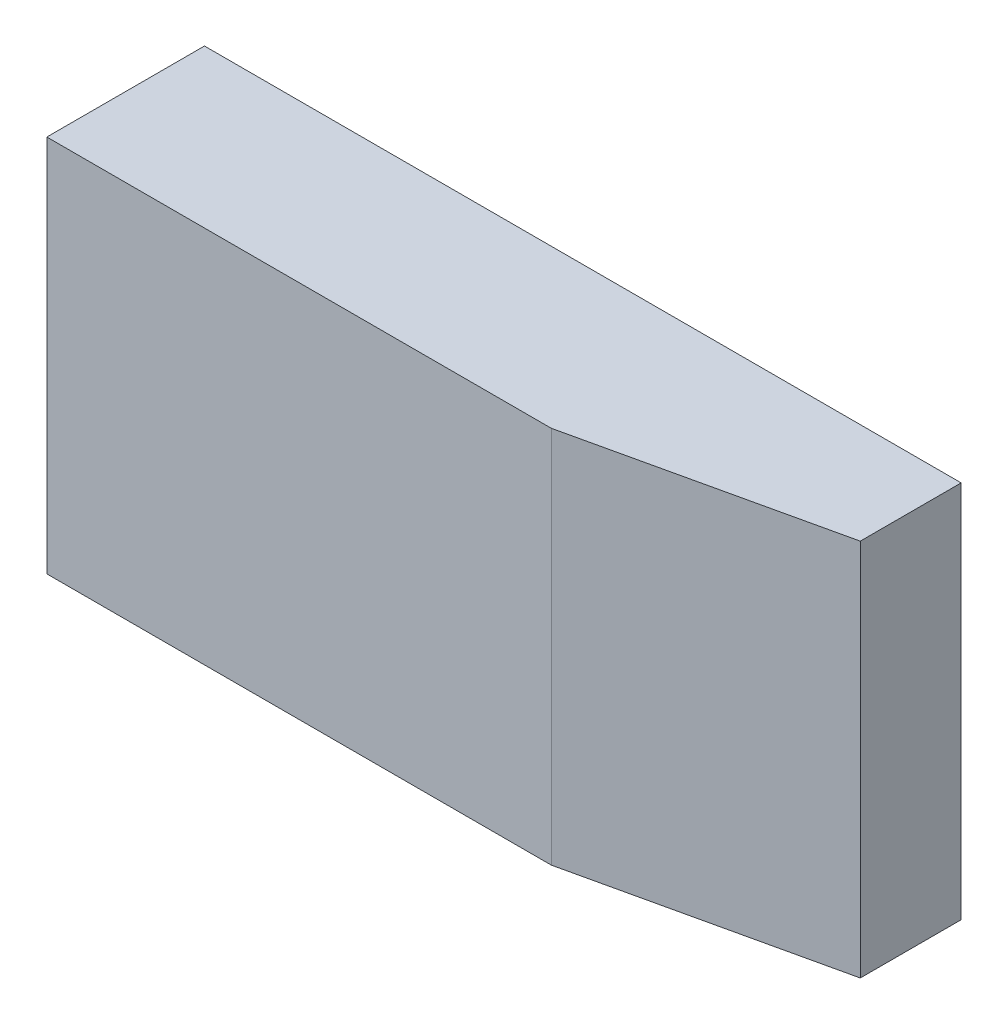
SolidWorks part; units mm, degrees
ref_plane "Front Plane" through (0, 0, 0) normal (1, 0, 0) x (0, 1, 0)
ref_plane "Top Plane" through (0, 0, 0) normal (0, 0, 1) x (0, 1, 0)
ref_plane "Right Plane" through (0, 0, 0) normal (0, 1, 0) x (-1, 0, 0)
sketch "Sketch1" plane through (0, 0, 0) normal (0, 1, 0) x (-1, 0, 0)
  line L0 (0, 0) -> (0, 8)
  line L1 (0, 8) -> (20, 12.5)
  line L2 (20, 12.5) -> (60, 12.5)
  line L3 (60, 12.5) -> (60, 0)
  line L4 (60, 0) -> (0, 0)
  point P3 (10, 10.2969)
  dimension "D1" = 60
  dimension "D2" = 40
  dimension "D3" = 8
  dimension "D4" = 12.5
extrude "Boss-Extrude1" add sketch "Sketch1" along normal blind 30
